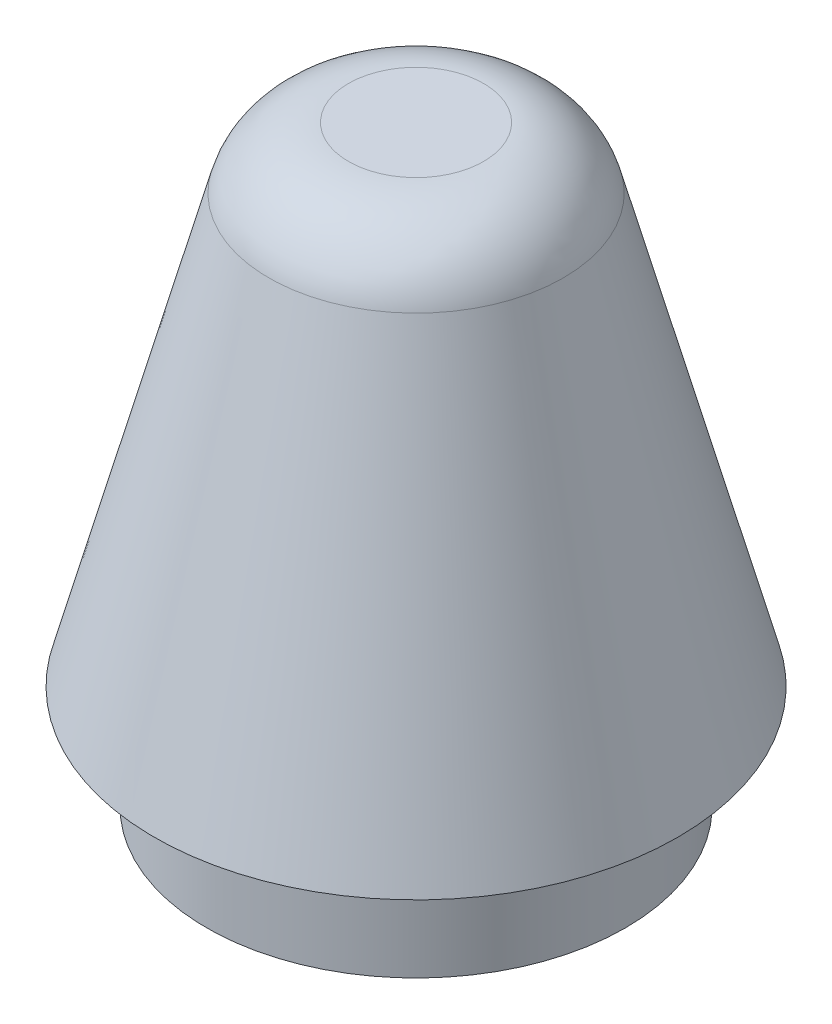
SolidWorks part; units mm, degrees
ref_plane "Front Plane" through (0, 0, 0) normal (0, 0, 1) x (1, 0, 0)
ref_plane "Top Plane" through (0, 0, 0) normal (0, 1, 0) x (1, 0, 0)
ref_plane "Right Plane" through (0, 0, 0) normal (1, 0, 0) x (0, 0, -1)
sketch "Sketch1" plane through (0, 0, 0) normal (0, 0, 1) x (1, 0, 0)
  line L0 (0, 0) -> (0, 29.6232)
  line L1 (0, 29.6232) -> (7.9375, 29.6232)
  line L2 (7.9375, 29.6232) -> (15.875, 0)
  line L3 (15.875, 0) -> (12.7, 0)
  line L4 (12.7, 0) -> (12.7, -6.35)
  line L5 (12.7, -6.35) -> (0, -6.35)
  line L6 (0, -6.35) -> (0, 0)
  dimension "D1" = 12.7
  dimension "D2" = 15.875
  dimension "D3" = 15
  dimension "D4" = 6.35
  dimension "D5" = 7.9375
revolve "Revolve1" add sketch "Sketch1" angle 360 about L0
fillet "Fillet1" radius 5 1 edges at (7.9375, 29.6232, 0)
